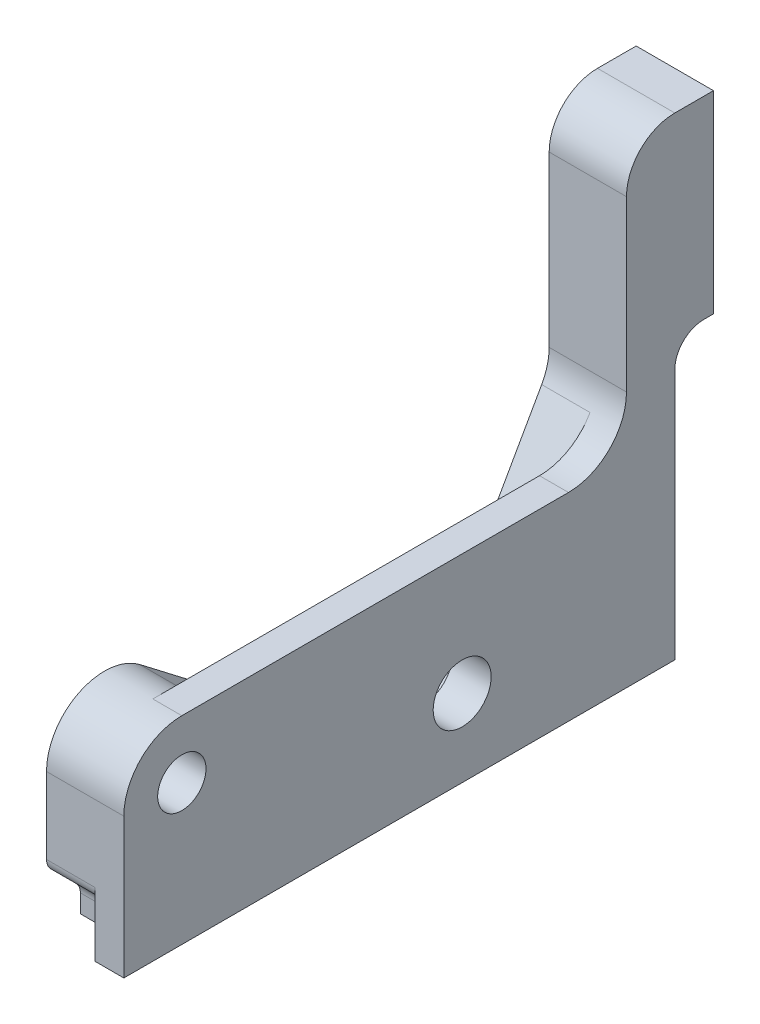
SolidWorks part; units mm, degrees
material "POM Acetal Copolymer"
ref_plane "Front Plane" through (0, 0, 0) normal (0, 0, 1) x (1, 0, 0)
ref_plane "Top Plane" through (0, 0, 0) normal (0, 1, 0) x (1, 0, 0)
ref_plane "Right Plane" through (0, 0, 0) normal (1, 0, 0) x (0, 0, -1)
sketch "Sketch1" plane through (0, 0, 0) normal (1, 0, 0) x (0, 0, -1)
  line L1 (0, 0) -> (61, 0)
  line L2 (0, 0) -> (0, 49)
  line L3 (0, 49) -> (61, 49)
  line L4 (61, 0) -> (61, 49)
  circle A0 centre (6, 14.5) radius 2.5
  circle A1 centre (35, 8) radius 3
  dimension "D1" = 6
  dimension "D2" = 5
  dimension "D3" = 14.5
  dimension "D4" = 6
  dimension "D5" = 8
  dimension "D6" = 35
  dimension "D7" = 61
  dimension "D8" = 49
extrude "Boss-Extrude1" add sketch "Sketch1" along normal blind 8
sketch "Sketch2" plane through (8, 0, 0) normal (1, 0, 0) x (0, 0, -1)
  line L0 (0, 49) -> (0, 0) construction
  line L2 (6, 20.5) -> (46, 20.5)
  line L4 (0, 14.5) -> (0, 50)
  line L5 (0, 50) -> (52, 50)
  line L6 (52, 50) -> (52, 26.5)
  line L7 (61, 49) -> (0, 49) construction
  arc A0 (0, 14.5) -> (6, 20.5) centre (6, 14.5) cw
  circle A1 centre (35, 8) radius 5 construction
  circle A2 centre (6, 14.5) radius 2.5 construction
  arc A4 (46, 20.5) -> (52, 26.5) centre (46, 26.5) ccw
  dimension "D2" = 10
  dimension "D1" = 1
  dimension "D3" = 52
extrude "Cut-Extrude1" cut sketch "Sketch2" against normal up to next
sketch "Sketch3" plane through (8, 0, 0) normal (1, 0, 0) x (0, 0, -1)
  line L57 (61, 0) -> (57, 0)
  line L58 (61, 0) -> (61, 29)
  line L59 (61, 29) -> (57, 29)
  line L60 (57, 0) -> (57, 29)
  dimension "D1" = 29
  dimension "D2" = 4
extrude "Cut-Extrude2" cut sketch "Sketch3" against normal up to next
fillet "Fillet1" radius 5 1 edges at (4, 49, -52)
fillet "Fillet2" radius 3 1 edges at (4, 29, -57)
hole_wizard "Tap Drill for M3 Tap1" positions "Sketch5" profile "Sketch4" hole size "M3" standard "ISO"
sketch "Sketch5" plane through (0, 0, 0) normal (0, -1, 0) x (-1, 0, 0)
  line L1 (-8, 0) -> (0, 0) construction
  line L2 (-8, 0) -> (-8, 57) construction
  point P0 (-4, 48)
  point P2 (-4, 12)
  dimension "D1" = 4
  dimension "D2" = 12
  dimension "D3" = 36
sketch "Sketch4" plane through (4, 0, -48) normal (1, 0, 0) x (0, 0, -1)
  line L0 (0, 0) -> (0, 10.7511)
  line L1 (0, 10.7511) -> (1.25, 10)
  line L2 (1.25, 10) -> (1.25, 0)
  line L5 (1.25, 0) -> (0, 0)
  line L10 (0, 10.7511) -> (-1.25, 10) construction
  line L11 (0, -6.35) -> (0, 107.95) construction
  dimension "Hole Dia." = 2.5
  dimension "Hole Depth" = 10
  dimension "Drill Angle" = 118
hole_wizard "Tap Drill for M3 Tap2" positions "Sketch8" profile "Sketch7" hole size "M3" standard "ISO"
sketch "Sketch8" plane through (0, 0, -61) normal (0, 0, -1) x (-1, 0, 0)
  line L0 (-8, 49) -> (0, 49) construction
  line L1 (0, 29) -> (-8, 29) construction
  line L3 (0, 29) -> (0, 49) construction
  point P0 (-4, 44)
  point P2 (-4, 34)
  dimension "D1" = 5
  dimension "D2" = 5
  dimension "D3" = 4
sketch "Sketch7" plane through (4, 44, -61) normal (1, 0, 0) x (0, 1, 0)
  line L0 (0, 0) -> (0, 8.7511)
  line L1 (0, 8.7511) -> (1.25, 8)
  line L2 (1.25, 8) -> (1.25, 0)
  line L5 (1.25, 0) -> (0, 0)
  line L10 (0, 8.7511) -> (-1.25, 8) construction
  line L11 (0, -6.35) -> (0, 107.95) construction
  dimension "Hole Dia." = 2.5
  dimension "Hole Depth" = 8
  dimension "Drill Angle" = 118
sketch "Sketch9" plane through (0, 0, 0) normal (-1, 0, 0) x (0, 0, 1)
  line L0 (-51.2271, 23.5542) -> (-40.6626, 4.8087)
  line L1 (-31.0425, 2.8436) -> (-9.653, 19.2598)
  line L2 (0, 14.5) -> (0, 0) construction
  line L3 (-52, 26.5) -> (-52, 44) construction
  line L4 (-52, 26.5) -> (0, 26.5)
  line L5 (0, 26.5) -> (0, 14.5)
  line L6 (0, 6) -> (-3.5, 2.5)
  line L7 (-3.5, 2.5) -> (-3.5, 0)
  line L8 (0, 0) -> (-57, 0) construction
  line L9 (-3.5, 0) -> (0, 0)
  line L10 (0, 0) -> (0, 6)
  arc A0 (-52, 26.5) -> (-51.2271, 23.5542) centre (-46, 26.5) ccw
  arc A1 (-52, 26.5) -> (-46, 20.5) centre (-46, 26.5) ccw construction
  arc A2 (-40.6626, 4.8087) -> (-31.0425, 2.8436) centre (-35, 8) ccw
  arc A3 (-9.653, 19.2598) -> (0, 14.5) centre (-6, 14.5) cw
  dimension "D1" = 6.5
  dimension "D2" = 3.5
  dimension "D3" = 45
  dimension "D4" = 6
extrude "Cut-Extrude3" cut sketch "Sketch9" against normal blind 5
sketch "Sketch10" plane through (5, 0, 0) normal (-1, 0, 0) x (0, 0, 1)
  line L0 (-51.2271, 23.5542) -> (-40.6626, 4.8087) construction
  line L1 (-31.0425, 2.8436) -> (-9.653, 19.2598) construction
  line L2 (-42.7018, 8.427) -> (-40.6626, 4.8087)
  line L3 (-31.0425, 2.8436) -> (-27.7477, 5.3723)
  line L4 (-31.0425, 2.8436) -> (-9.653, 19.2598) construction
  circle A0 centre (-35, 8) radius 3
  arc A1 (-39.9193, 8.8949) -> (-30.1238, 6.894) centre (-35, 8) cw
  circle A2 centre (-35, 8) radius 3 construction
  arc A5 (-39.9193, 8.8949) -> (-42.7018, 8.427) centre (-41.395, 9.1634) cw
  arc A6 (-30.1238, 6.894) -> (-27.7477, 5.3723) centre (-28.661, 6.5622) ccw
  arc A7 (-40.6626, 4.8087) -> (-31.0425, 2.8436) centre (-35, 8) ccw
  dimension "D1" = 1.5
  dimension "D2" = 5
extrude "Boss-Extrude2" add sketch "Sketch10" along normal blind 1
fillet "Fillet3" radius 1.5 2 edges at (2.5, 2.5, -3.5) (2.5, 6, 0)
